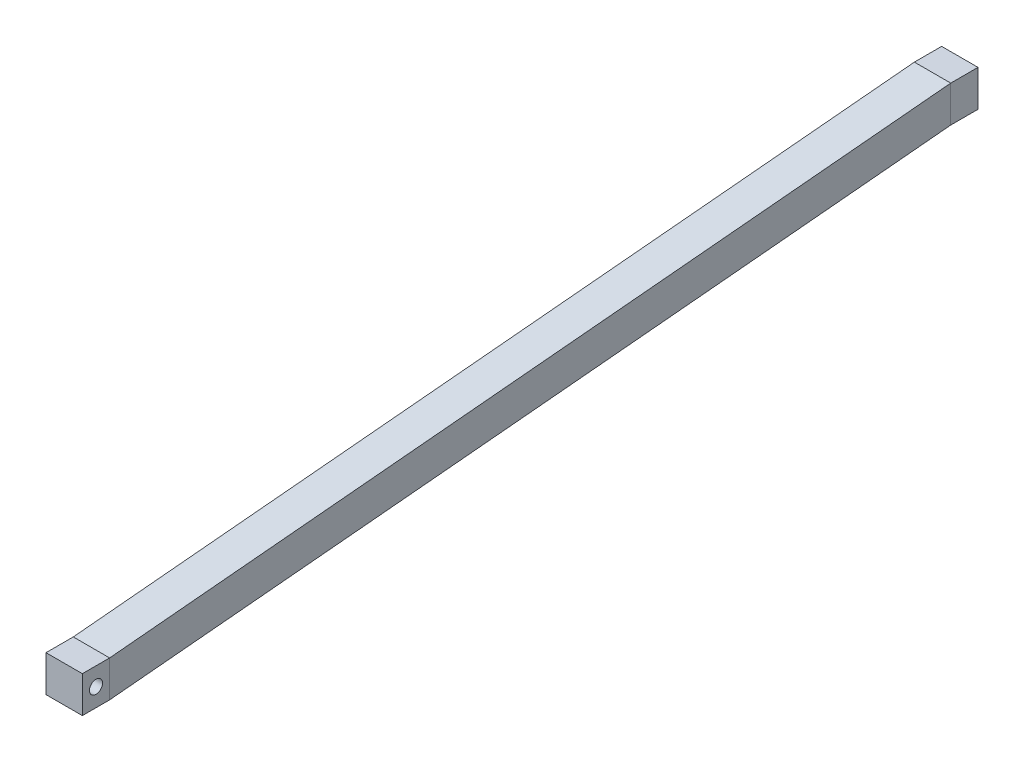
SolidWorks part; units mm, degrees
ref_plane "Front Plane" through (0, 0, 0) normal (0, 0, 1) x (1, 0, 0)
ref_plane "Top Plane" through (0, 0, 0) normal (0, 1, 0) x (1, 0, 0)
ref_plane "Right Plane" through (0, 0, 0) normal (1, 0, 0) x (0, 0, -1)
sketch "Sketch26" plane through (0, 0, 0) normal (0, 0, 1) x (1, 0, 0)
  line L1 (-6.35, 6.35) -> (6.35, 6.35)
  line L2 (-6.35, 6.35) -> (-6.35, -6.35)
  line L3 (-6.35, -6.35) -> (6.35, -6.35)
  line L4 (6.35, 6.35) -> (6.35, -6.35)
  line L5 (-6.35, 6.35) -> (6.35, -6.35) construction
  line L6 (-6.35, -6.35) -> (6.35, 6.35) construction
  point P0 (0, 0)
  point P6 (6.35, -6.35)
  dimension "D1" = 12.7
  dimension "D2" = 12.7
ref_plane "Plane3" through (0, 0, 238.2458) normal (0, 0, 1) x (1, 0, 0)
sketch "Sketch27" plane through (0, 0, 238.2458) normal (0, 0, 1) x (1, 0, 0)
  line L1 (-49.2125, -88.9) -> (-61.9125, -88.9)
  line L2 (-49.2125, -88.9) -> (-49.2125, -76.2)
  line L3 (-49.2125, -76.2) -> (-61.9125, -76.2)
  line L4 (-61.9125, -88.9) -> (-61.9125, -76.2)
  line L5 (-49.2125, -88.9) -> (-61.9125, -76.2) construction
  line L6 (-49.2125, -76.2) -> (-61.9125, -88.9) construction
  point P0 (-55.5625, -82.55)
  point P5 (23.427, -20.8125)
  point P6 (73.89, -63.8883)
  point P7 (9.1311, -2.0562)
  point P9 (-46.8398, -50.3083)
  point P10 (23.427, -83.2108)
  point P11 (40.0649, -66.2975)
  dimension "D1" = 12.7
  dimension "D2" = 12.7
  dimension "D3" = 49.2125
  dimension "D4" = 76.2
loft "Loft1" add profiles "Sketch26", "Sketch27"
sketch "Sketch28" plane through (0, 0, 0) normal (0, 0, -1) x (-1, 0, 0)
  line L1 (-6.35, 6.35) -> (6.35, 6.35)
  line L2 (-6.35, 6.35) -> (-6.35, -6.35)
  line L3 (-6.35, -6.35) -> (6.35, -6.35)
  line L4 (6.35, 6.35) -> (6.35, -6.35)
extrude "Boss-Extrude5" add sketch "Sketch28" along normal blind 9.525
sketch "Sketch29" plane through (0, 0, 238.2458) normal (0, 0, 1) x (1, 0, 0)
  line L1 (-61.9125, -76.2) -> (-49.2125, -76.2)
  line L2 (-61.9125, -76.2) -> (-61.9125, -88.9)
  line L3 (-61.9125, -88.9) -> (-49.2125, -88.9)
  line L4 (-49.2125, -76.2) -> (-49.2125, -88.9)
  point P6 (-49.2125, -76.2)
  point P7 (0, 0)
extrude "Boss-Extrude6" add sketch "Sketch29" along normal blind 9.525
sketch "Sketch30" plane through (-49.2125, 0, 0) normal (1, 0, 0) x (0, 0, -1)
  line L0 (-247.7708, -76.2) -> (-238.2458, -88.9) construction
  circle A0 centre (-243.0083, -82.55) radius 2.286
  point P4 (-243.0083, -82.55)
  dimension "D1" = 4.572
extrude "Cut-Extrude7" cut sketch "Sketch30" against normal through all
sketch "Sketch31" plane through (0, 0, -9.525) normal (0, 0, -1) x (-1, 0, 0)
  circle A0 centre (0, 0) radius 1.905
  dimension "D1" = 3.81
extrude "Cut-Extrude8" cut sketch "Sketch31" against normal blind 12.7
